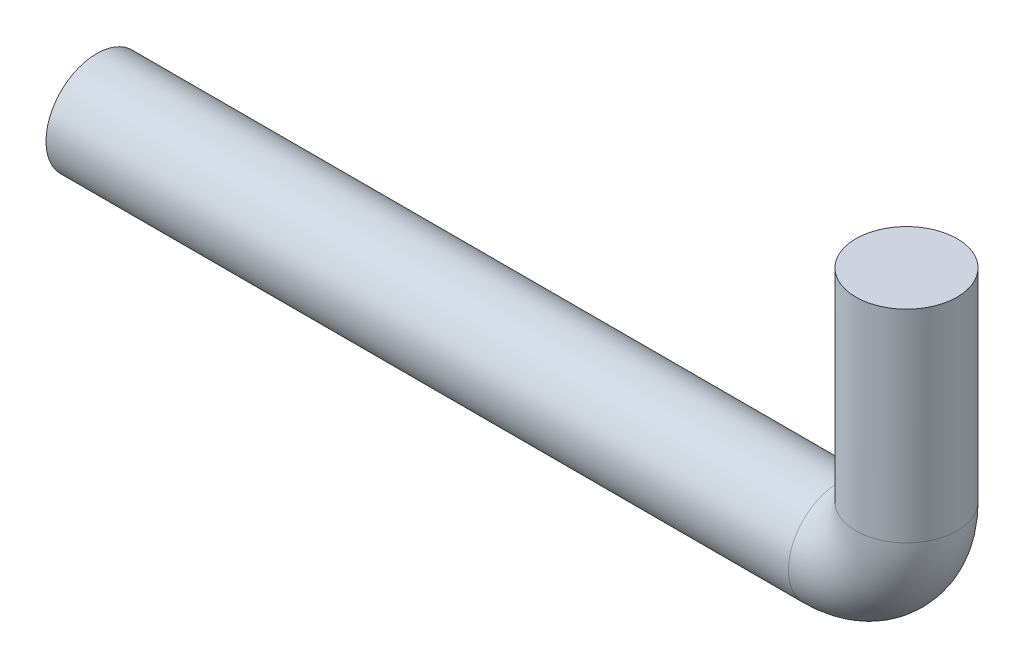
SolidWorks part; units mm, degrees
ref_plane "Front Plane" through (0, 0, 0) normal (0, 0, 1) x (1, 0, 0)
ref_plane "Top Plane" through (0, 0, 0) normal (0, 1, 0) x (1, 0, 0)
ref_plane "Right Plane" through (0, 0, 0) normal (1, 0, 0) x (0, 0, -1)
sketch "Sketch1" plane through (0, 0, 0) normal (0, 0, 1) x (1, 0, 0)
  line L0 (0, 12.7) -> (0, 50.8)
  line L1 (-12.7, 0) -> (-152.4, 0)
  arc A0 (0, 12.7) -> (-12.7, 0) centre (-12.7, 12.7) cw
  point P6 (0, 0)
  point P7 (0, 0)
  point P8 (0, 0)
  dimension "D3" = 12.7
  dimension "D1" = 50.8
  dimension "D2" = 152.4
sweep "Sweep5" add path "Sketch1" circular profile diameter 19.05 parameters "D3"=19.05
